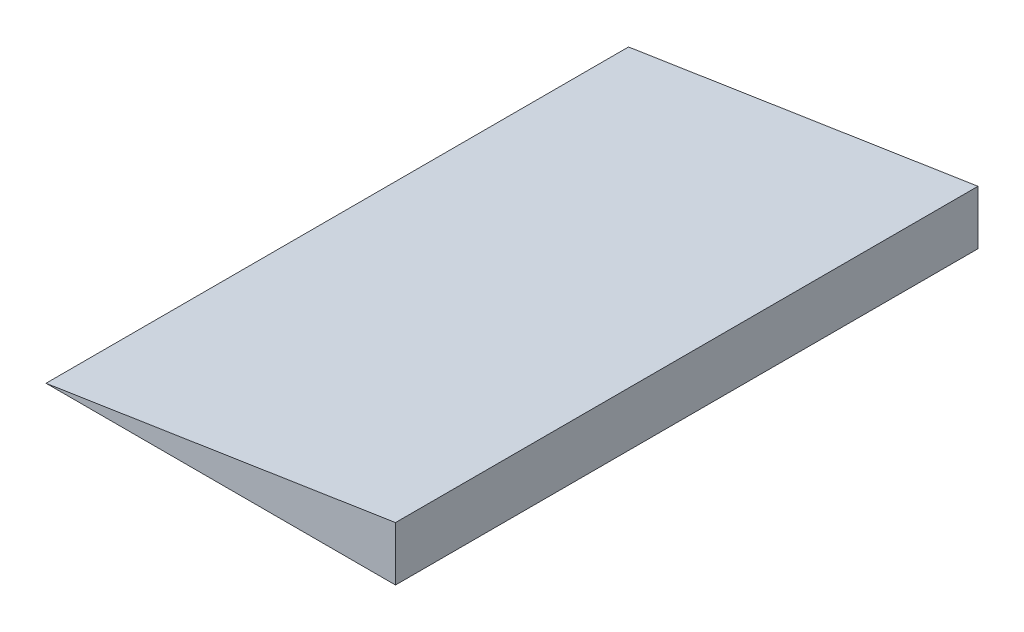
SolidWorks part; units mm, degrees
ref_plane "Front Plane" through (0, 0, 0) normal (0, 0, 1) x (1, 0, 0)
ref_plane "Top Plane" through (0, 0, 0) normal (0, 1, 0) x (1, 0, 0)
ref_plane "Right Plane" through (0, 0, 0) normal (1, 0, 0) x (0, 0, -1)
sketch "Sketch1" plane through (0, 0, 0) normal (0, 0, 1) x (1, 0, 0)
  line L0 (0, 0) -> (30, 4.6442)
  line L1 (30, 4.6442) -> (30, 0)
  line L2 (30, 0) -> (0, 0)
  dimension "D1" = 8.8
  dimension "D2" = 30
extrude "Boss-Extrude1" add sketch "Sketch1" along normal blind 50
